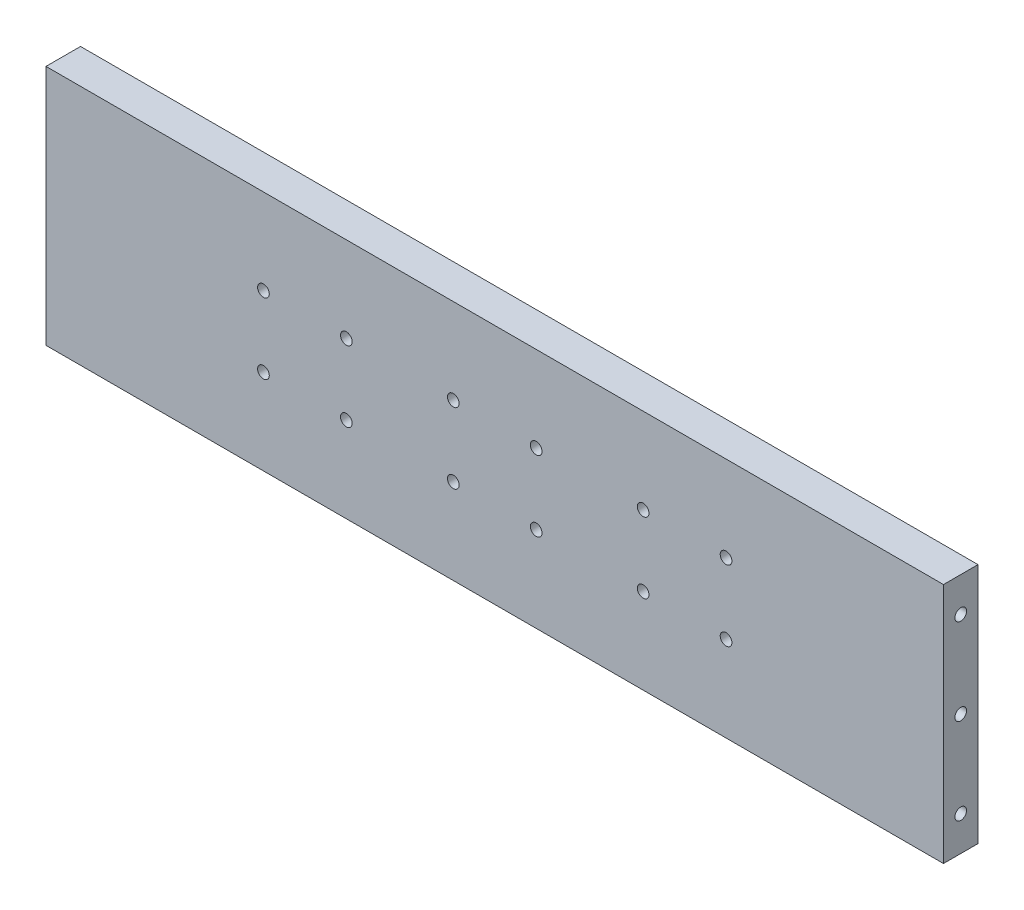
SolidWorks part; units mm, degrees
ref_plane "Front Plane" through (0, 0, 0) normal (0, 0, 1) x (1, 0, 0)
ref_plane "Top Plane" through (0, 0, 0) normal (0, 1, 0) x (1, 0, 0)
ref_plane "Right Plane" through (0, 0, 0) normal (1, 0, 0) x (0, 0, -1)
sketch "Sketch1" plane through (0, 0, 0) normal (0, 0, 1) x (1, 0, 0)
  line L1 (0, 0) -> (330.2, 0)
  line L2 (0, 0) -> (0, 88.9)
  line L3 (0, 88.9) -> (330.2, 88.9)
  line L4 (330.2, 0) -> (330.2, 88.9)
  dimension "D1" = 88.9
  dimension "D2" = 330.2
extrude "Boss-Extrude1" add sketch "Sketch1" along normal blind 12.7
sketch "Sketch3" plane through (0, 0, 0) normal (-1, 0, 0) x (0, 0, 1)
  line L0 (0, 88.9) -> (0, 0) construction
  line L1 (12.7, 88.9) -> (0, 88.9) construction
  line L2 (12.7, 0) -> (0, 0) construction
  circle A0 centre (6.35, 76.2) radius 2.1463
  circle A1 centre (6.35, 12.7) radius 2.1463
  circle A2 centre (6.35, 44.45) radius 2.1463
  dimension "D7" = 4.2926
  dimension "D8" = 4.2926
  dimension "D9" = 4.2926
  dimension "D1" = 6.35
  dimension "D2" = 12.7
  dimension "D3" = 12.7
  dimension "D4" = 6.35
  dimension "D5" = 6.35
  dimension "D6" = 44.45
extrude "Cut-Extrude1" cut sketch "Sketch3" against normal blind 38.1
sketch "Sketch5" plane through (330.2, 0, 0) normal (1, 0, 0) x (0, 0, -1)
  line L0 (0, 0) -> (0, 88.9) construction
  line L1 (-12.7, 88.9) -> (0, 88.9) construction
  line L2 (-12.7, 0) -> (0, 0) construction
  circle A0 centre (-6.35, 76.2) radius 2.1463
  circle A1 centre (-6.35, 12.7) radius 2.1463
  circle A2 centre (-6.35, 44.45) radius 2.1463
  dimension "D7" = 4.2926
  dimension "D8" = 4.2926
  dimension "D9" = 4.2926
  dimension "D1" = 6.35
  dimension "D2" = 6.35
  dimension "D3" = 6.35
  dimension "D4" = 12.7
  dimension "D5" = 12.7
  dimension "D6" = 44.45
extrude "Cut-Extrude2" cut sketch "Sketch5" against normal blind 38.1
sketch "Sketch6" plane through (0, 0, 0) normal (0, 0, -1) x (-1, 0, 0)
  circle A4 centre (-250.2, 57.45) radius 2.1463
  circle A5 centre (-219.7, 57.45) radius 2.1463
  circle A6 centre (-219.7, 31.45) radius 2.1463
  circle A7 centre (-250.2, 31.45) radius 2.1463
  circle A16 centre (-180.35, 57.45) radius 2.1463
  circle A17 centre (-149.85, 57.45) radius 2.1463
  circle A18 centre (-149.85, 31.45) radius 2.1463
  circle A19 centre (-180.35, 31.45) radius 2.1463
  circle A20 centre (-110.5, 31.45) radius 2.1463
  circle A21 centre (-110.5, 57.45) radius 2.1463
  circle A22 centre (-80, 57.45) radius 2.1463
  circle A23 centre (-80, 31.45) radius 2.1463
extrude "Cut-Extrude3" cut sketch "Sketch6" against normal through all
